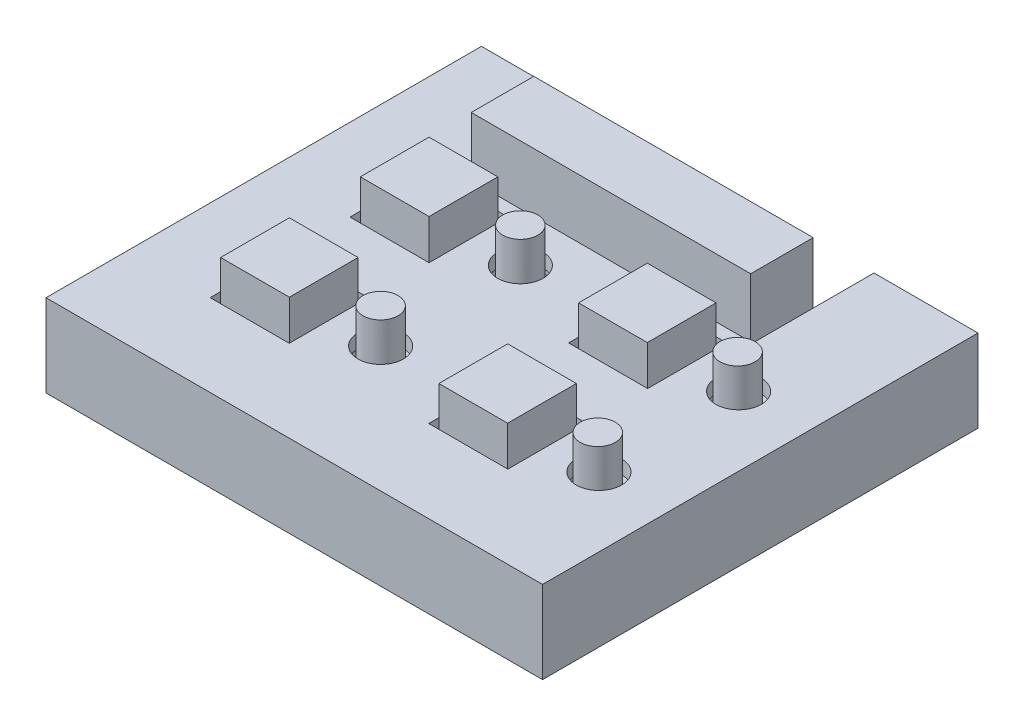
SolidWorks part; units mm, degrees
ref_plane "Front Plane" through (0, 0, 0) normal (0, 0, 1) x (1, 0, 0)
ref_plane "Top Plane" through (0, 0, 0) normal (0, 1, 0) x (1, 0, 0)
ref_plane "Right Plane" through (0, 0, 0) normal (1, 0, 0) x (0, 0, -1)
sketch "Sketch1" plane through (0, 0, 0) normal (0, 1, 0) x (1, 0, 0)
  line L1 (-31.115, -26.67) -> (31.115, -26.67)
  line L2 (-31.115, -26.67) -> (-31.115, 26.67)
  line L3 (-31.115, 26.67) -> (31.115, 26.67)
  line L4 (31.115, -26.67) -> (31.115, 26.67)
  line L5 (-31.115, -26.67) -> (31.115, 26.67) construction
  line L6 (-31.115, 26.67) -> (31.115, -26.67) construction
  point P0 (0, 0)
  dimension "D1" = 62.23
  dimension "D2" = 53.34
extrude "Boss-Extrude1" add sketch "Sketch1" along normal blind 1.57
sketch "Sketch2" plane through (0, 1.57, 0) normal (0, 1, 0) x (1, 0, 0)
  line L0 (-31.115, 26.67) -> (-31.115, -26.67) construction
  line L1 (-23.415, -8.97) -> (-13.415, -8.97)
  line L2 (-23.415, -8.97) -> (-23.415, -18.97)
  line L3 (-23.415, -18.97) -> (-13.415, -18.97)
  line L4 (-13.415, -8.97) -> (-13.415, -18.97)
  line L5 (-23.415, -8.97) -> (-13.415, -18.97) construction
  line L6 (-23.415, -18.97) -> (-13.415, -8.97) construction
  line L7 (-31.115, -26.67) -> (31.115, -26.67) construction
  line L8 (8.335, -8.97) -> (18.335, -8.97)
  line L9 (8.335, -8.97) -> (8.335, -18.97)
  line L10 (8.335, -18.97) -> (18.335, -18.97)
  line L11 (18.335, -8.97) -> (18.335, -18.97)
  line L12 (8.335, 11.35) -> (18.335, 11.35)
  line L13 (8.335, 11.35) -> (8.335, 1.35)
  line L14 (8.335, 1.35) -> (18.335, 1.35)
  line L15 (18.335, 11.35) -> (18.335, 1.35)
  line L16 (-23.415, 11.35) -> (-13.415, 11.35)
  line L17 (-23.415, 11.35) -> (-23.415, 1.35)
  line L18 (-23.415, 1.35) -> (-13.415, 1.35)
  line L19 (-13.415, 11.35) -> (-13.415, 1.35)
  line L20 (31.115, -26.67) -> (31.115, 26.67) construction
  point P0 (-18.415, -13.97)
  dimension "D1" = 7.7
  dimension "D2" = 7.7
  dimension "D3" = 10
  dimension "D4" = 10
  dimension "D7" = 12.78
  dimension "D8" = 21.75
  dimension "D9" = 10.32
  dimension "D5" = 2
  dimension "D6" = 2
extrude "Boss-Extrude2" add sketch "Sketch2" along normal blind 12.5
sketch "Sketch3" plane through (0, 1.57, 0) normal (0, 1, 0) x (1, 0, 0)
  line L0 (31.115, -26.67) -> (31.115, 26.67) construction
  line L1 (-31.115, 26.67) -> (-31.115, -26.67) construction
  line L2 (-5.715, -13.4039) -> (26.0346, -13.5598) construction
  circle A0 centre (-5.715, -13.4039) radius 2.55
  circle A1 centre (26.0346, -13.5598) radius 2.55
  circle A2 centre (26.0484, 6.7602) radius 2.55
  circle A3 centre (-5.7012, 6.9161) radius 2.55
  dimension "D1" = 25.4
  dimension "D2" = 5.1
  dimension "D7" = 5.0804
  dimension "D5" = 31.75
  dimension "D6" = 20.32
  dimension "D3" = 2
  dimension "D4" = 2
extrude "Boss-Extrude3" add sketch "Sketch3" along normal blind 12.5
sketch "Sketch4" plane through (0, 1.57, 0) normal (0, 1, 0) x (1, 0, 0)
  line L0 (-31.115, -26.67) -> (31.115, -26.67) construction
  line L1 (-20.955, 24.13) -> (19.685, 24.13)
  line L2 (-20.955, 24.13) -> (-20.955, 15.03)
  line L3 (-20.955, 15.03) -> (19.685, 15.03)
  line L4 (19.685, 24.13) -> (19.685, 15.03)
  line L5 (-31.115, 26.67) -> (-31.115, -26.67) construction
  dimension "D1" = 9.1
  dimension "D2" = 40.64
  dimension "D3" = 41.7
  dimension "D4" = 10.16
extrude "Boss-Extrude4" add sketch "Sketch4" along normal blind 15
sketch "Sketch5" plane through (0, 1.57, 0) normal (0, 1, 0) x (1, 0, 0)
  line L0 (-31.115, 26.67) -> (-31.115, -26.67) construction
  line L1 (31.115, 26.67) -> (-31.115, 26.67) construction
  line L2 (-31.115, -26.67) -> (31.115, -26.67) construction
  line L3 (31.115, -26.67) -> (31.115, 26.67) construction
  circle A0 centre (-24.765, 21.59) radius 1.5
  circle A1 centre (-28.575, -24.13) radius 1.5
  circle A2 centre (28.575, -24.13) radius 1.5
  circle A3 centre (28.575, 21.59) radius 1.5
  dimension "D1" = 6.35
  dimension "D3" = 3
  dimension "D6" = 3
  dimension "D9" = 3
  dimension "D12" = 3
  dimension "D2" = 5.08
  dimension "D4" = 2.54
  dimension "D5" = 2.54
  dimension "D7" = 2.54
  dimension "D8" = 2.54
  dimension "D10" = 2.54
  dimension "D11" = 5.08
extrude "Cut-Extrude1" cut sketch "Sketch5" against normal through all
ref_plane "Plane1" through (0, 9, 0) normal (0, 1, 0) x (1, 0, 0)
sketch "Sketch6" plane through (0, 9, 0) normal (0, 1, 0) x (1, 0, 0)
  line L0 (-31.115, 26.67) -> (-31.115, -26.67) construction
  line L1 (-36.115, 31.67) -> (36.115, 31.67)
  line L2 (-36.115, 31.67) -> (-36.115, -31.67)
  line L3 (-36.115, -31.67) -> (36.115, -31.67)
  line L4 (36.115, 31.67) -> (36.115, -31.67)
  line L5 (31.115, 26.67) -> (-31.115, 26.67) construction
  line L6 (31.115, -26.67) -> (31.115, 26.67) construction
  line L7 (-31.115, -26.67) -> (31.115, -26.67) construction
  dimension "D1" = 5
  dimension "D2" = 5
  dimension "D3" = 5
  dimension "D4" = 5
extrude "Boss-Extrude5" add sketch "Sketch6" against normal blind 12 separate body
sketch "Sketch7" plane through (0, -3, 0) normal (0, -1, 0) x (1, 0, 0)
  line L14 (34.115, -29.67) -> (34.115, 29.67)
  line L15 (-34.115, -29.67) -> (34.115, -29.67)
  line L16 (-34.115, 29.67) -> (-34.115, -29.67)
  line L17 (34.115, 29.67) -> (-34.115, 29.67)
  line L18 (34.115, -29.67) -> (34.115, 29.67)
  line L19 (-34.115, -29.67) -> (34.115, -29.67)
  line L20 (-34.115, 29.67) -> (-34.115, -29.67)
  line L21 (34.115, 29.67) -> (-34.115, 29.67)
  dimension "D1" = 2
extrude "Cut-Extrude2" cut sketch "Sketch7" against normal blind 10
sketch "Sketch8" plane through (0, 9, 0) normal (0, 1, 0) x (1, 0, 0)
  line L0 (-5.7012, 6.9161) -> (26.0488, 6.9161) construction
  line L1 (-5.7012, 6.9161) -> (-5.7012, -13.4039) construction
  line L2 (36.115, 31.67) -> (-36.115, 31.67) construction
  line L3 (-22.2076, 31.67) -> (20.9884, 31.67)
  line L4 (-22.2076, 31.67) -> (-22.2076, 14.0213)
  line L5 (-22.2076, 14.0213) -> (20.9884, 14.0213)
  line L6 (20.9884, 31.67) -> (20.9884, 14.0213)
  line L84 (7.585, 0.6462) -> (19.085, 0.6462)
  line L85 (19.085, 0.6462) -> (19.085, 12.1462)
  line L86 (19.085, 12.1462) -> (7.585, 12.1462)
  line L87 (7.585, 12.1462) -> (7.585, 0.6462)
  line L88 (-24.165, 12.1) -> (-24.165, 0.6)
  line L89 (-24.165, 0.6) -> (-12.665, 0.6)
  line L90 (-12.665, 0.6) -> (-12.665, 12.1)
  line L91 (-12.665, 12.1) -> (-24.165, 12.1)
  line L92 (-24.165, 12.1) -> (-24.165, 0.6)
  line L93 (-24.165, 0.6) -> (-12.665, 0.6)
  line L94 (-12.665, 0.6) -> (-12.665, 12.1)
  line L95 (-12.665, 12.1) -> (-24.165, 12.1)
  line L96 (7.5649, -19.6738) -> (19.0649, -19.6738)
  line L97 (19.0649, -19.6738) -> (19.0649, -8.1738)
  line L98 (19.0649, -8.1738) -> (7.5649, -8.1738)
  line L99 (7.5649, -8.1738) -> (7.5649, -19.6738)
  line L100 (-24.1851, -19.72) -> (-12.6851, -19.72)
  line L101 (-12.6851, -19.72) -> (-12.6851, -8.22)
  line L102 (-12.6851, -8.22) -> (-24.1851, -8.22)
  line L103 (-24.1851, -8.22) -> (-24.1851, -19.72)
  line L104 (-24.165, 0.6) -> (7.585, 0.6462) construction
  circle A0 centre (26.0488, 6.9161) radius 3.3
  circle A1 centre (26.0488, -13.4039) radius 3.3
  circle A2 centre (-5.7012, 6.9161) radius 3.3
  circle A3 centre (-5.7012, 6.9161) radius 3.3
  circle A4 centre (-5.7012, -13.4039) radius 3.3
  dimension "D4" = 31.75
  dimension "D8" = 31.75
  dimension "D9" = 20.32
  dimension "D1" = 0.75
  dimension "D5" = 0.75
  dimension "D2" = 2
  dimension "D3" = 2
  dimension "D6" = 2
  dimension "D7" = 2
extrude "Cut-Extrude3" cut sketch "Sketch8" against normal through all
ref_plane "Plane2" through (0, 1.6, 0) normal (0, 1, 0) x (1, 0, 0)
sketch "Sketch9" plane through (0, 1.6, 0) normal (0, 1, 0) x (1, 0, 0)
  line L1 (-31.115, 26.67) -> (-22.9001, 26.67)
  line L2 (-31.115, 26.67) -> (-31.115, 18.2745)
  line L3 (-31.115, 18.2745) -> (-22.9001, 18.2745)
  line L4 (-22.9001, 26.67) -> (-22.9001, 18.2745)
  line L5 (-31.115, -26.67) -> (-25.4299, -26.67)
  line L6 (-31.115, -26.67) -> (-31.115, -20.5529)
  line L7 (-31.115, -20.5529) -> (-25.4299, -20.5529)
  line L8 (-25.4299, -26.67) -> (-25.4299, -20.5529)
  line L9 (31.115, -26.67) -> (25.4299, -26.67)
  line L10 (31.115, -26.67) -> (31.115, -20.5529)
  line L11 (31.115, -20.5529) -> (25.4299, -20.5529)
  line L12 (25.4299, -26.67) -> (25.4299, -20.5529)
  line L13 (31.115, 26.67) -> (25.1686, 26.67)
  line L14 (31.115, 26.67) -> (31.115, 18.4628)
  line L15 (31.115, 18.4628) -> (25.1686, 18.4628)
  line L16 (25.1686, 26.67) -> (25.1686, 18.4628)
  circle A33 centre (-24.765, 21.59) radius 1
  circle A34 centre (-24.765, 21.59) radius 1
  circle A36 centre (-28.575, -24.13) radius 1
  circle A37 centre (-28.575, -24.13) radius 1
  circle A39 centre (28.575, -24.13) radius 1
  circle A40 centre (28.575, -24.13) radius 1
  circle A42 centre (28.575, 21.59) radius 1
  circle A43 centre (28.575, 21.59) radius 1
  dimension "D1" = 0.5
  dimension "D2" = 0.5
  dimension "D3" = 0.5
  dimension "D4" = 0.5
extrude "Boss-Extrude6" add sketch "Sketch9" along normal blind 6 separate body
